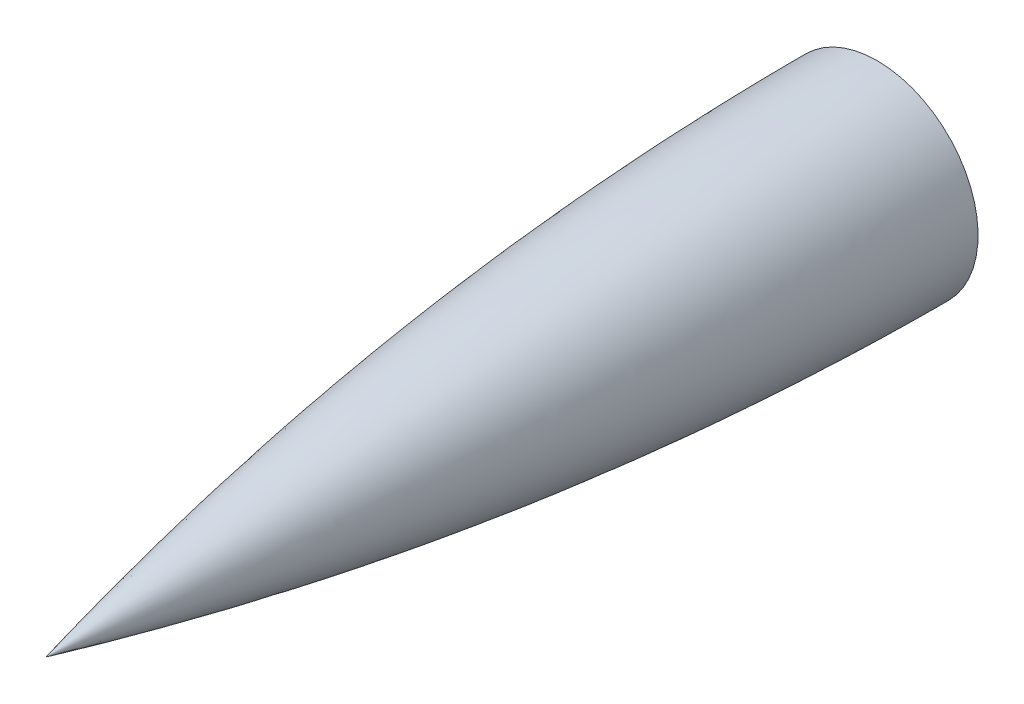
SolidWorks part; units mm, degrees
ref_plane "Front Plane" through (0, 0, 0) normal (0, 0, 1) x (1, 0, 0)
ref_plane "Top Plane" through (0, 0, 0) normal (0, 1, 0) x (1, 0, 0)
ref_plane "Right Plane" through (0, 0, 0) normal (1, 0, 0) x (0, 0, -1)
sketch "Sketch1" plane through (0, 0, 0) normal (1, 0, 0) x (0, 0, -1)
  line L0 (0, 50.8) -> (0, 0)
  line L1 (0, 0) -> (-419.1, 0)
  spline S0 degree 2 poles (-460.1592, -10.4413) (-209.1246, 56.3777) (41.91, 50.292) knots 0 0 0 1 1 1 construction
  spline S1 degree 2 poles (-419.1, 0) (-209.55, 50.8) (0, 50.8) knots 0.08178 0.08178 0.08178 0.916525 0.916525 0.916525
  dimension "D1" = 50.8
revolve "Revolve1" add sketch "Sketch1" angle 360 about L1
equation "\"Kprime\"= 1"
equation "\"R\"= 2'radius of the base"
equation "\"L\" = 16.5'overall length"
